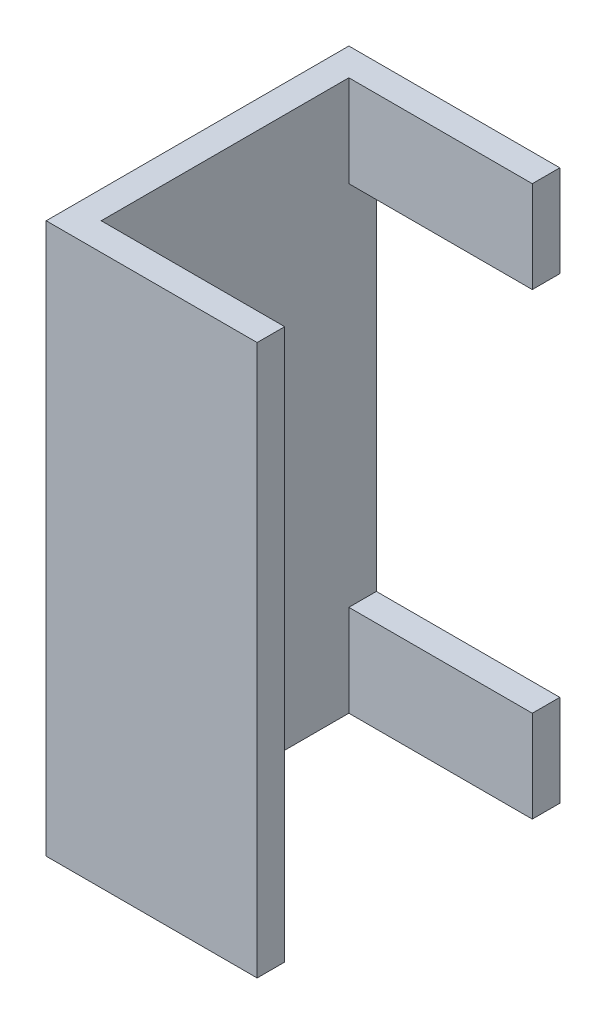
SolidWorks part; units mm, degrees
ref_plane "Plan de face" through (0, 0, 0) normal (0, 0, 1) x (1, 0, 0)
ref_plane "Plan de dessus" through (0, 0, 0) normal (0, 1, 0) x (1, 0, 0)
ref_plane "Plan de droite" through (0, 0, 0) normal (1, 0, 0) x (0, 0, -1)
sketch "Esquisse1" plane through (0, 0, 0) normal (0, 0, 1) x (1, 0, 0)
  line L1 (-44.0586, 39.1) -> (-21.0586, 39.1)
  line L2 (-44.0586, 39.1) -> (-44.0586, -20.9)
  line L3 (-44.0586, -20.9) -> (-21.0586, -20.9)
  line L4 (-21.0586, 39.1) -> (-21.0586, -20.9)
  line L5 (-41.0586, 29.1) -> (-21.0586, 29.1)
  line L6 (-41.0586, 29.1) -> (-41.0586, -10.9)
  line L7 (-41.0586, -10.9) -> (-21.0586, -10.9)
  line L8 (-21.0586, 29.1) -> (-21.0586, -10.9)
  dimension "D1" = 23
  dimension "D2" = 60
  dimension "D3" = 40
  dimension "D4" = 10
  dimension "D5" = 20
  dimension "D6" = 3
extrude "Boss.-Extru.1" add sketch "Esquisse1" along normal blind 36 contours L7 L6 L5 L4 L1 L2 L3
sketch "Esquisse2" plane through (0, 0, 36) normal (0, 0, 1) x (1, 0, 0)
  line L1 (-21.0586, 39.1) -> (-41.0586, 39.1)
  line L2 (-21.0586, 39.1) -> (-21.0586, 29.1)
  line L3 (-21.0586, 29.1) -> (-41.0586, 29.1)
  line L4 (-41.0586, 39.1) -> (-41.0586, 29.1)
extrude "Enlèv. mat.-Extru.1" cut sketch "Esquisse2" against normal blind 33
sketch "Esquisse3" plane through (0, 0, 36) normal (0, 0, 1) x (1, 0, 0)
  line L1 (-41.0586, -10.9) -> (-21.0586, -10.9)
  line L2 (-41.0586, -10.9) -> (-41.0586, -20.9)
  line L3 (-41.0586, -20.9) -> (-21.0586, -20.9)
  line L4 (-21.0586, -10.9) -> (-21.0586, -20.9)
extrude "Enlèv. mat.-Extru.2" cut sketch "Esquisse3" against normal blind 33
sketch "Esquisse4" plane through (-41.0586, 0, 0) normal (1, 0, 0) x (0, 0, -1)
  line L0 (-3, 39.1) -> (-36, 39.1) construction
  line L1 (-36, -20.9) -> (-33, -20.9)
  line L2 (-36, -20.9) -> (-36, 39.1)
  line L3 (-36, 39.1) -> (-33, 39.1)
  line L4 (-33, -20.9) -> (-33, 39.1)
  dimension "D1" = 3
sketch "Esquisse5" plane through (-41.0586, 0, 0) normal (1, 0, 0) x (0, 0, -1)
  line L0 (-3, -20.9) -> (-36, -20.9) construction
  line L1 (-36, 39.1) -> (-30, 39.1)
  line L2 (-36, 39.1) -> (-36, -20.9)
  line L3 (-36, -20.9) -> (-30, -20.9)
  line L4 (-30, 39.1) -> (-30, -20.9)
  dimension "D1" = 6
extrude "Boss.-Extru.3" add sketch "Esquisse5" along normal blind 20
sketch "Esquisse6" plane through (-21.0586, 0, 0) normal (1, 0, 0) x (0, 0, -1)
  line L0 (-36, -20.9) -> (-30, -20.9) construction
  line L1 (-36, 39.1) -> (-33, 39.1)
  line L2 (-36, 39.1) -> (-36, -20.9)
  line L3 (-36, -20.9) -> (-33, -20.9)
  line L4 (-33, 39.1) -> (-33, -20.9)
extrude "Enlèv. mat.-Extru.3" cut sketch "Esquisse6" against normal blind 50
